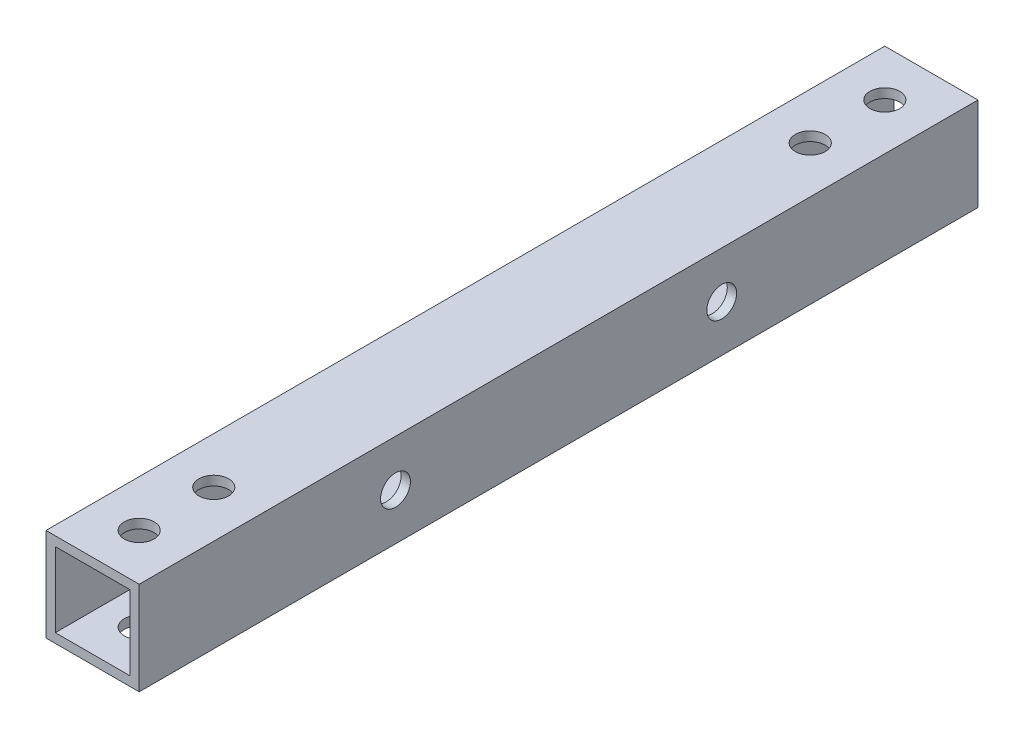
SolidWorks part; units mm, degrees
material "6061 合金"
ref_plane "正面" through (0, 0, 0) normal (0, 0, 1) x (1, 0, 0)
ref_plane "平面" through (0, 0, 0) normal (0, 1, 0) x (1, 0, 0)
ref_plane "右側面" through (0, 0, 0) normal (1, 0, 0) x (0, 0, -1)
sketch "断面 スケッチ" plane through (0, 0, 0) normal (0, 0, 1) x (1, 0, 0)
  line L1 (-5, -5) -> (5, -5)
  line L2 (-5, -5) -> (-5, 5)
  line L3 (-5, 5) -> (5, 5)
  line L4 (5, -5) -> (5, 5)
  line L5 (-5, -5) -> (5, 5) construction
  line L6 (-5, 5) -> (5, -5) construction
  point P0 (0, 0)
  dimension "D1" = 10
extrude "フレーム全長" add sketch "断面 スケッチ" along normal blind 90 thin thin type one direction reverse wall 1
sketch "上面穴 スケッチ" plane through (0, 5, 0) normal (0, 1, 0) x (1, 0, 0)
  line L0 (0, 0) -> (0, -90) construction
  line L1 (5, 0) -> (-5, 0) construction
  line L2 (5, -90) -> (-5, -90) construction
  line L3 (-5, -45) -> (5, -45) construction
  line L4 (-5, -90) -> (-5, 0) construction
  line L5 (5, -90) -> (5, 0) construction
  circle A0 centre (0, -5) radius 1.6
  circle A1 centre (0, -85) radius 1.6
  circle A2 centre (0, -13) radius 1.6
  circle A3 centre (0, -77) radius 1.6
  dimension "D1" = 5
  dimension "D2" = 3.2
  dimension "D3" = 8
  dimension "D4" = 8
sketch "側面穴 スケッチ" plane through (5, 0, 0) normal (1, 0, 0) x (0, 0, -1)
  line L0 (0, 0) -> (-90, 0) construction
  line L1 (0, -5) -> (0, 5) construction
  line L2 (-90, -5) -> (-90, 5) construction
  line L3 (-45, 5) -> (-45, -5) construction
  line L4 (-90, 5) -> (0, 5) construction
  line L5 (-90, -5) -> (0, -5) construction
  circle A0 centre (-27.5, 0) radius 1.6
  circle A1 centre (-62.5, 0) radius 1.6
  dimension "D1" = 17.5
  dimension "D2" = 3.2
extrude "上面穴貫通" cut sketch "上面穴 スケッチ" against normal through all
extrude "側面穴貫通" cut sketch "側面穴 スケッチ" against normal through all
fillet "フィレット" [suppressed] radius 5
